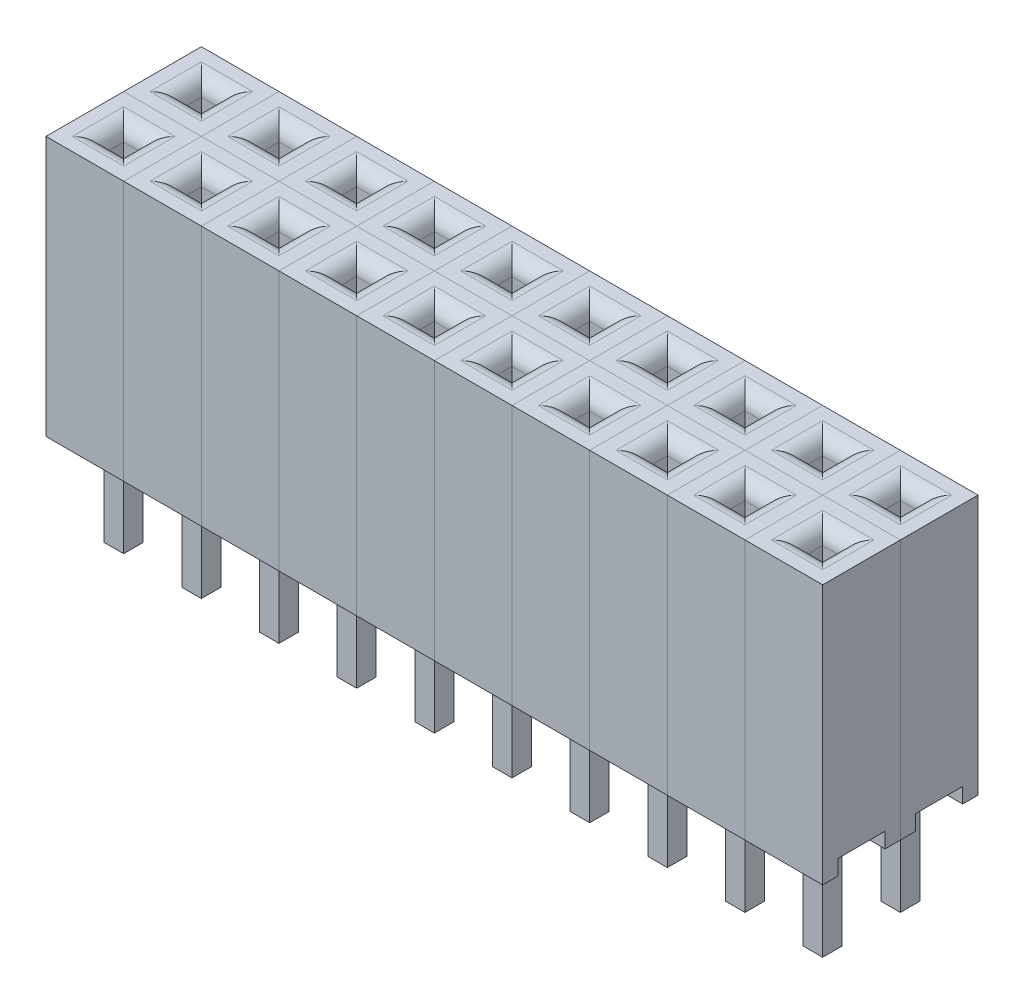
SolidWorks part; units mm, degrees
ref_plane "前视基准面" through (0, 0, 0) normal (0, 0, 1) x (1, 0, 0)
ref_plane "上视基准面" through (0, 0, 0) normal (0, 1, 0) x (1, 0, 0)
ref_plane "右视基准面" through (0, 0, 0) normal (1, 0, 0) x (0, 0, -1)
sketch "草图1" plane through (0, 0, 0) normal (0, 1, 0) x (1, 0, 0)
  line L1 (1.27, -1.27) -> (-1.27, -1.27)
  line L2 (1.27, -1.27) -> (1.27, 1.27)
  line L3 (1.27, 1.27) -> (-1.27, 1.27)
  line L4 (-1.27, -1.27) -> (-1.27, 1.27)
  line L5 (1.27, -1.27) -> (-1.27, 1.27) construction
  line L6 (1.27, 1.27) -> (-1.27, -1.27) construction
  point P0 (0, 0)
  dimension "D1" = 2.54
  dimension "D2" = 2.54
extrude "凸台-拉伸1" add sketch "草图1" along normal blind 8.5
sketch "草图3" plane through (0, 0, 0) normal (1, 0, 0) x (0, 0, -1)
  line L0 (1.27, 0) -> (-1.27, 0) construction
  line L1 (0.77, 0) -> (-0.77, 0)
  line L2 (0.77, 0) -> (0.77, 0.5)
  line L3 (0.77, 0.5) -> (-0.77, 0.5)
  line L4 (-0.77, 0) -> (-0.77, 0.5)
  line L5 (0, 1.1304) -> (0, -1.1304) construction
  line L6 (1.27, 8.5) -> (1.27, 0) construction
  point P10 (0, 0)
  dimension "D1" = 0.5
  dimension "D2" = 0.5
extrude "切除-拉伸2" cut sketch "草图3" against normal through all both and the other way through all
sketch "草图2" plane through (0, 8.5, 0) normal (0, 1, 0) x (1, 0, 0)
  line L1 (-0.34, -0.34) -> (0.34, -0.34)
  line L2 (-0.34, -0.34) -> (-0.34, 0.34)
  line L3 (-0.34, 0.34) -> (0.34, 0.34)
  line L4 (0.34, -0.34) -> (0.34, 0.34)
  line L5 (-0.34, -0.34) -> (0.34, 0.34) construction
  line L6 (-0.34, 0.34) -> (0.34, -0.34) construction
  point P0 (0, 0)
  dimension "D1" = 0.68
extrude "切除-拉伸1" cut sketch "草图2" against normal offset from surface (7 mm away) 1.5 up to face at (0, 0, -1.02)
sketch "草图4" plane through (0, 0, 0) normal (1, 0, 0) x (0, 0, -1)
  line L0 (-0.13, 0.6425) -> (0.32, 0.3425)
  line L1 (0.77, 0.5) -> (-0.77, 0.5) construction
  line L2 (0.32, 0.3425) -> (0.32, -3)
  line L3 (0.32, -3) -> (-0.32, -3)
  line L4 (-0.32, -3) -> (-0.32, 0)
  line L5 (-0.32, 0) -> (-0.77, 0.3)
  line L6 (-0.77, 0.5) -> (-0.77, 0) construction
  line L7 (-0.32, 0) -> (0.035, 0.5325) construction
  line L8 (-0.13, 0.6425) -> (-0.13, 0.5)
  line L9 (-0.13, 0.5) -> (-0.77, 0.5)
  line L10 (0, 3.0819) -> (0, -3.0819) construction
  line L11 (-0.77, 0.5) -> (-0.77, 0.3)
  point P17 (0, 0)
  dimension "D1" = 3
  dimension "D2" = 0.64
  dimension "D3" = 0.2
extrude "凸台-拉伸2" add sketch "草图4" along normal mid plane 0.64
fillet "圆角1" radius 0.5 4 edges at (0, 8.5, -0.34) (-0.34, 8.5, 0) (0.34, 8.5, 0) (0, 8.5, 0.34)
pattern_linear "阵列(线性)1" count 10 spacing 2.54 along (1, 0, 0) count 2 spacing 2.54 along (0, 0, 1) of bodies 109
sketch "草图5" plane through (0, 8.5, 0) normal (0, 1, 0) x (1, 0, 0)
  line L0 (0, 1.4076) -> (0, -1.4076) construction
  line L1 (-0.2, 1.035) -> (0.2, 1.035)
  line L2 (-0.2, 1.035) -> (-0.2, 0.635)
  line L3 (-0.2, 0.635) -> (0.2, 0.635)
  line L4 (0.2, 1.035) -> (0.2, 0.635)
  line L5 (-0.2, -0.635) -> (0.2, -0.635)
  line L6 (-0.2, -0.635) -> (-0.2, -1.035)
  line L7 (-0.2, -1.035) -> (0.2, -1.035)
  line L8 (0.2, -0.635) -> (0.2, -1.035)
  line L9 (-1.1668, 0) -> (1.1668, 0) construction
  point P12 (0, 0)
  point P15 (0, 0)
  dimension "D1" = 1.27
  dimension "D2" = 0.4
extrude "切除-拉伸3" [suppressed] cut sketch "草图5" against normal offset from surface (7 mm away) 1.5
fillet "圆角2" [suppressed] radius 0.1
sketch "草图6" [suppressed] plane through (0, 0, 0) normal (1, 0, 0) x (0, 0, -1)
  line L0 (0.77, 0.5) -> (0.91, 0)
  line L1 (0.77, 0) -> (0.77, 0.5) construction
  line L2 (0.91, 0) -> (0.91, -2.3)
  line L3 (0.91, -2.3) -> (0.76, -2.3)
  line L4 (0.76, -2.3) -> (0.76, -0.0206)
  line L5 (0.76, -0.0206) -> (0.6142, 0.5)
  line L6 (0.7587, 0.5404) -> (0.6142, 0.5) construction
  line L7 (0, 2.9618) -> (0, -2.9618) construction
  line L8 (0.77, 0.5) -> (-0.77, 0.5) construction
  line L9 (0.835, 1.5) -> (0.835, -3.1463) construction
  line L10 (0.635, 1.5) -> (1.035, 1.5) construction
  line L11 (-0.835, 1.5) -> (-0.835, -3.1463) construction
  line L12 (-1.035, 1.5) -> (-0.635, 1.5) construction
  line L13 (0.77, 0.5) -> (0.6142, 0.5)
  line L14 (-0.7587, 0.5404) -> (-0.6142, 0.5) construction
  line L15 (-0.76, -0.0206) -> (-0.6142, 0.5)
  line L16 (-0.76, -2.3) -> (-0.76, -0.0206)
  line L17 (-0.91, -2.3) -> (-0.76, -2.3)
  line L18 (-0.91, 0) -> (-0.91, -2.3)
  line L19 (-0.77, 0.5) -> (-0.91, 0)
  line L20 (-0.77, 0.5) -> (-0.6142, 0.5)
  point P14 (0, 0)
  dimension "D1" = 0.15
  dimension "D2" = 2.3
extrude "凸台-拉伸3" [suppressed] add sketch "草图6" along normal mid plane 0.4
pattern_linear "阵列(线性)2" [suppressed] count 10 spacing 2.54 count 2 spacing 2.54
